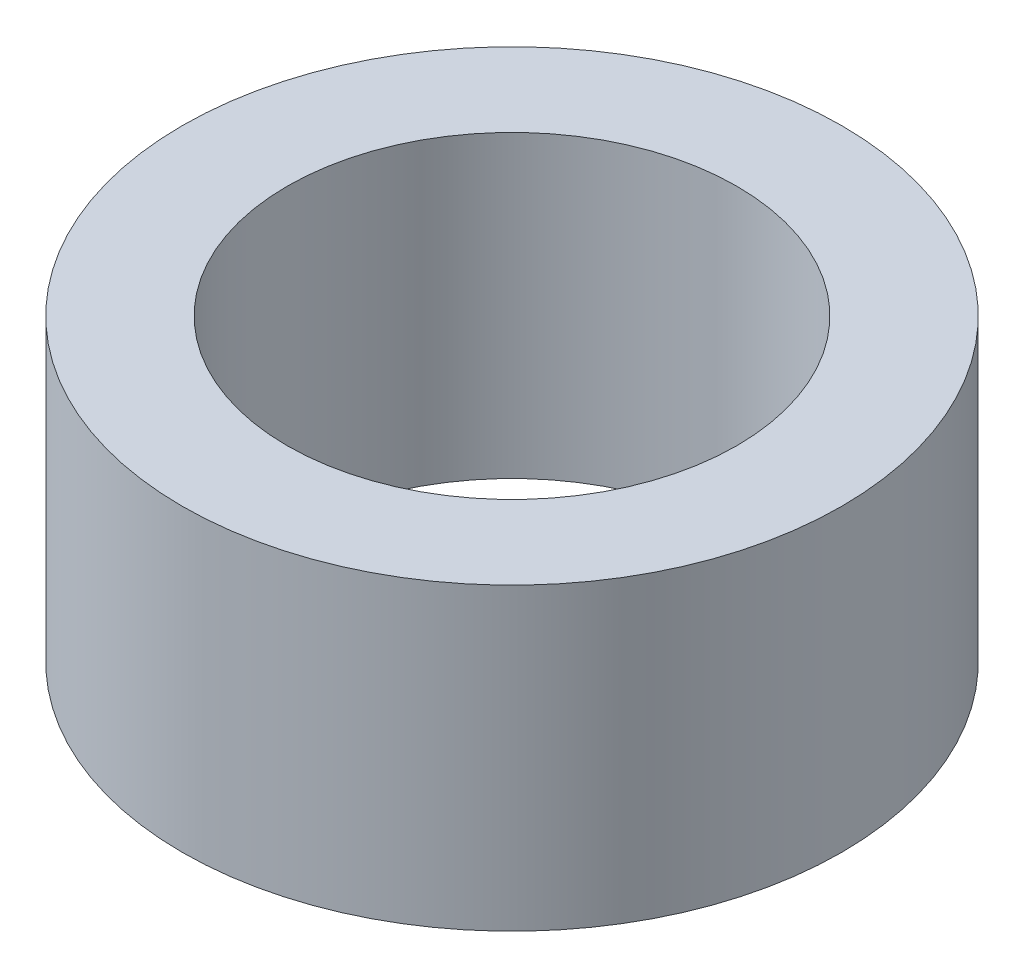
SolidWorks part; units mm, degrees
ref_plane "Front Plane" through (0, 0, 0) normal (0, 0, 1) x (1, 0, 0)
ref_plane "Top Plane" through (0, 0, 0) normal (0, 1, 0) x (1, 0, 0)
ref_plane "Right Plane" through (0, 0, 0) normal (1, 0, 0) x (0, 0, -1)
sketch "Sketch1" plane through (0, 0, 0) normal (0, 1, 0) x (1, 0, 0)
  circle A0 centre (0, 0) radius 11
extrude "Boss-Extrude1" add sketch "Sketch1" along normal blind 10
sketch "Sketch2" plane through (0, 10, 0) normal (0, 1, 0) x (1, 0, 0)
  circle A0 centre (0, 0) radius 7.5
extrude "Cut-Extrude1" cut sketch "Sketch2" against normal blind 10
